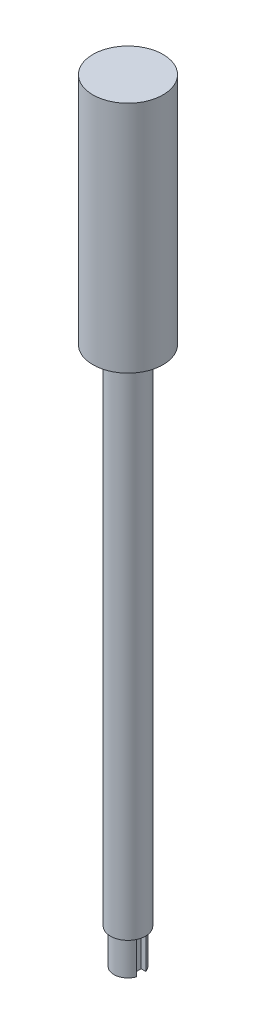
SolidWorks part; units mm, degrees
ref_plane "Front Plane" through (0, 0, 0) normal (0, 0, 1) x (1, 0, 0)
ref_plane "Top Plane" through (0, 0, 0) normal (0, 1, 0) x (1, 0, 0)
ref_plane "Right Plane" through (0, 0, 0) normal (1, 0, 0) x (0, 0, -1)
sketch "Sketch1" plane through (0, 0, 0) normal (0, 1, 0) x (1, 0, 0)
  circle A1 centre (0, 0) radius 7.5
  dimension "D1" = 15
extrude "Boss-Extrude1" add sketch "Sketch1" along normal blind 215.44
sketch "Sketch5" plane through (0, 215.44, 0) normal (0, 1, 0) x (1, 0, 0)
  circle A2 centre (0, 0) radius 15
  dimension "D1" = 30
extrude "Boss-Extrude5" add sketch "Sketch5" along normal blind 5
sketch "Sketch6" plane through (0, 220.44, 0) normal (0, 1, 0) x (1, 0, 0)
  circle A0 centre (0, 0) radius 12.5
  circle A1 centre (0, 0) radius 15
  circle A2 centre (0, 0) radius 15
  dimension "D2" = 25
  dimension "D1" = 0
extrude "Boss-Extrude6" add sketch "Sketch6" along normal blind 90
sketch "Sketch7" plane through (0, 310.44, 0) normal (0, 1, 0) x (1, 0, 0)
  circle A1 centre (0, 0) radius 15
  circle A2 centre (0, 0) radius 15
  dimension "D1" = 0
extrude "Boss-Extrude7" add sketch "Sketch7" along normal blind 5
fillet "Fillet2" radius 2 1 edges at (0, 215.44, 7.5)
sketch "Sketch9" plane through (0, 0, 0) normal (0, -1, 0) x (1, 0, 0)
  circle A2 centre (0, 0) radius 6
  dimension "D1" = 12
extrude "Boss-Extrude9" add sketch "Sketch9" along normal blind 15
sketch "Sketch12" plane through (0, -15, 0) normal (0, -1, 0) x (1, 0, 0)
  line L1 (3.66, 2) -> (18.9533, 2)
  line L2 (3.66, 2) -> (3.66, -2)
  line L3 (3.66, -2) -> (18.9533, -2)
  line L4 (18.9533, 2) -> (18.9533, -2)
  point P4 (3.66, 0)
  dimension "D1" = 4
  dimension "D2" = 3.66
extrude "Cut-Extrude3" cut sketch "Sketch12" against normal up to surface (15 mm away) up to face at (0, 0, 6)
